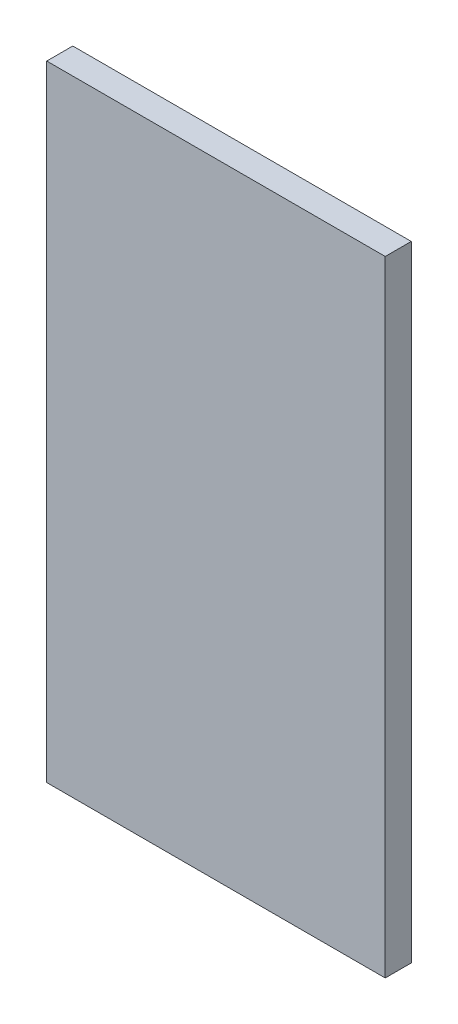
SolidWorks part; units mm, degrees
ref_plane "Front Plane" through (0, 0, 0) normal (0, 0, 1) x (1, 0, 0)
ref_plane "Top Plane" through (0, 0, 0) normal (0, 1, 0) x (1, 0, 0)
ref_plane "Right Plane" through (0, 0, 0) normal (1, 0, 0) x (0, 0, -1)
sketch "Sketch1" plane through (0, 0, 0) normal (0, 1, 0) x (1, 0, 0)
  line L1 (-48.3681, 30.6016) -> (34.1819, 30.6016)
  line L2 (-48.3681, 30.6016) -> (-48.3681, 24.2516)
  line L3 (-48.3681, 24.2516) -> (34.1819, 24.2516)
  line L4 (34.1819, 30.6016) -> (34.1819, 24.2516)
  dimension "D1" = 6.35
  dimension "D2" = 82.55
extrude "Boss-Extrude1" add sketch "Sketch1" along normal blind 152.4
